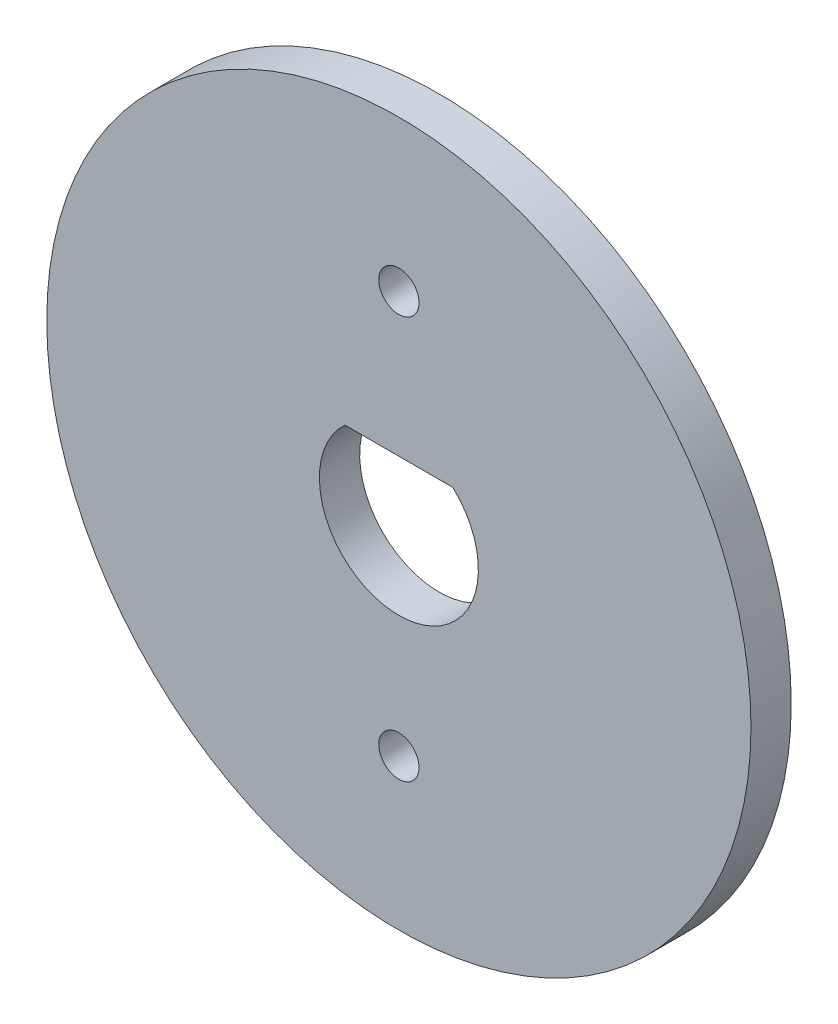
SolidWorks part; units mm, degrees
ref_plane "Спереди" through (0, 0, 0) normal (0, 0, 1) x (1, 0, 0)
ref_plane "Сверху" through (0, 0, 0) normal (0, 1, 0) x (1, 0, 0)
ref_plane "Справа" through (0, 0, 0) normal (1, 0, 0) x (0, 0, -1)
sketch "Эскиз1" plane through (0, 0, 0) normal (0, 0, 1) x (1, 0, 0)
  line L0 (0, 17.5) -> (0, -17.5) construction
  line L1 (2.6819, 2.9) -> (-2.6819, 2.9)
  circle A0 centre (0, 0) radius 17.5
  circle A1 centre (0, 0) radius 10 construction
  arc A2 (-2.6819, 2.9) -> (2.6819, 2.9) centre (0, 0) ccw
  circle A3 centre (0, 10) radius 1
  circle A4 centre (0, -10) radius 1
  dimension "D1" = 35
  dimension "D2" = 20
  dimension "D3" = 7.9
  dimension "D4" = 2
  dimension "D5" = 2
  dimension "D6" = 2.9
extrude "Бобышка-Вытянуть1" add sketch "Эскиз1" along normal blind 2
